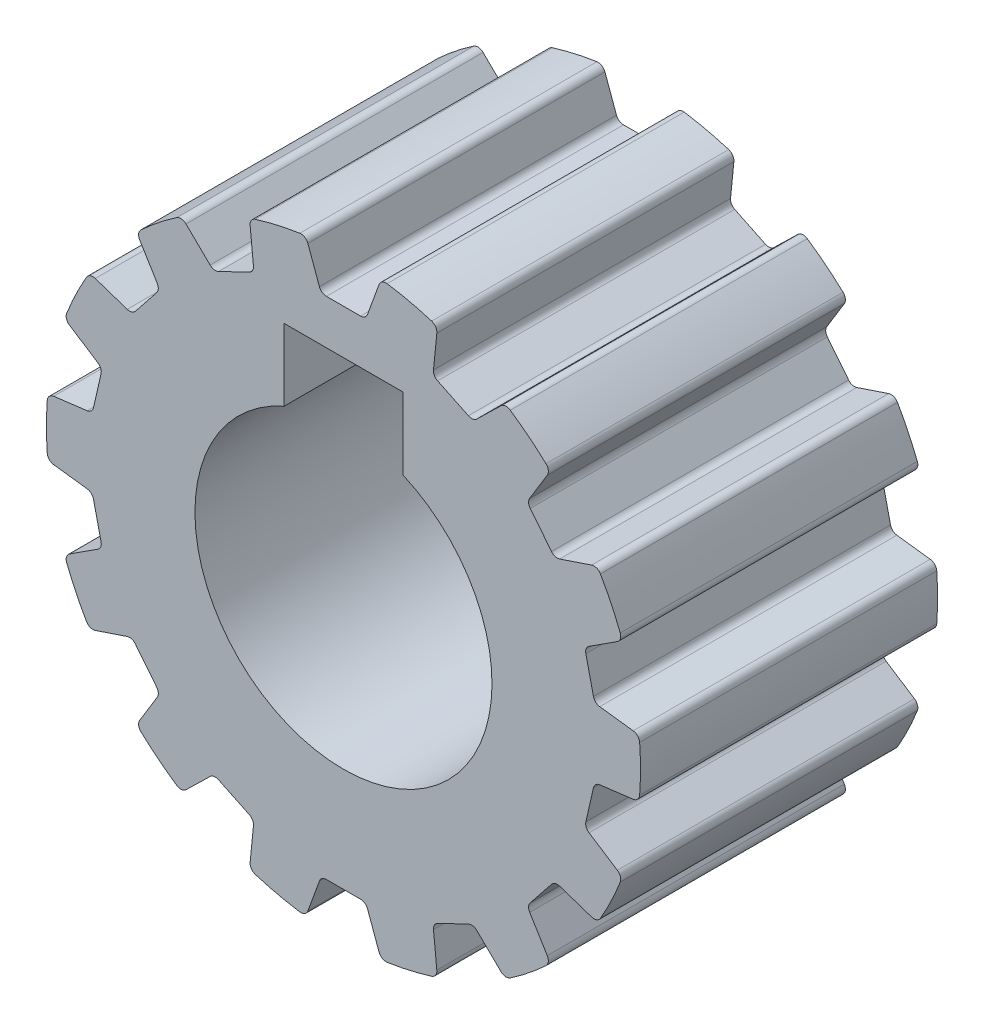
SolidWorks part; units mm, degrees
ref_plane "Front Plane" through (0, 0, 0) normal (0, 0, 1) x (1, 0, 0)
ref_plane "Top Plane" through (0, 0, 0) normal (0, 1, 0) x (1, 0, 0)
ref_plane "Right Plane" through (0, 0, 0) normal (1, 0, 0) x (0, 0, -1)
sketch "Sketch1" plane through (0, 0, 0) normal (0, 0, 1) x (1, 0, 0)
  line L0 (0, 0) -> (0, 6.4182) construction
  line L3 (-2, 4.5826) -> (-2, 7)
  line L4 (-2, 7) -> (2, 7)
  line L5 (2, 4.5826) -> (2, 7)
  circle A0 centre (0, 0) radius 10
  arc A1 (-2, 4.5826) -> (2, 4.5826) centre (0, 0) ccw
  point P5 (0, 4.4893)
  dimension "D1" = 20
  dimension "D2" = 10
  dimension "D3" = 4
  dimension "D4" = 7
extrude "Boss-Extrude1" add sketch "Sketch1" along normal blind 10
sketch "Sketch2" plane through (0, 0, 10) normal (0, 0, 1) x (1, 0, 0)
  line L0 (0, 0) -> (0, 10) construction
  line L1 (-1.2666, 9.9195) -> (-0.75, 8.5)
  line L2 (-0.75, 8.5) -> (0.75, 8.5)
  line L3 (0.75, 8.5) -> (1.2666, 9.9195)
  circle A0 centre (0, 0) radius 10 construction
  circle A1 centre (0, 0) radius 10
  circle M6 centre (0, 0) radius 10
  dimension "D1" = 20
  dimension "D2" = 20
  dimension "D3" = 1.5
  dimension "D4" = 8.5
extrude "Cut-Extrude1" cut sketch "Sketch2" against normal through all contours L2 L0 A1 L1 | L0 L2 L3 M6
pattern_circular "CirPattern1" count 14 over 360 about axis through (0, 0, 0) along (0, 0, 1) of "Cut-Extrude1"
fillet "Fillet1" radius 0.25 56 edges at (5.4451, 8.3875, 5) (4.3637, 7.3328, 5) (3.0123, 7.9836, 5) (3.1627, 9.4867, 5) (1.2666, 9.9195, 5) (0.75, 8.5, 5) (-0.75, 8.5, 5) (-3.1627, 9.4867, 5) (-3.0123, 7.9836, 5) (-4.3637, 7.3328, 5) (-6.9656, 7.175, 5) (-6.178, 5.886, 5) (-7.1132, 4.7133, 5) (-8.5451, 5.1944, 5) (-9.3889, 3.4422, 5) (-8.12, 2.6226, 5) (-8.4538, 1.1602, 5) (-9.9526, 0.9724, 5) (-9.9526, -0.9724, 5) (-8.4538, -1.1602, 5) (-8.12, -2.6226, 5) (-9.3889, -3.4422, 5) (-8.5451, -5.1944, 5) (-7.1132, -4.7133, 5) (-6.178, -5.886, 5) (-6.9656, -7.175, 5) (-5.4451, -8.3875, 5) (-4.3637, -7.3328, 5) (-3.0123, -7.9836, 5) (-3.1627, -9.4867, 5) (-1.2666, -9.9195, 5) (-0.75, -8.5, 5) (0.75, -8.5, 5) (1.2666, -9.9195, 5) (3.1627, -9.4867, 5) (3.0123, -7.9836, 5) (4.3637, -7.3328, 5) (5.4451, -8.3875, 5) (6.9656, -7.175, 5) (6.178, -5.886, 5) (7.1132, -4.7133, 5) (8.5451, -5.1944, 5) (9.3889, -3.4422, 5) (8.12, -2.6226, 5) (8.4538, -1.1602, 5) (9.9526, -0.9724, 5) (9.9526, 0.9724, 5) (8.4538, 1.1602, 5) (8.12, 2.6226, 5) (9.3889, 3.4422, 5) (8.5451, 5.1944, 5) (7.1132, 4.7133, 5) (6.178, 5.886, 5) (6.9656, 7.175, 5) (-5.4451, 8.3875, 5) (-1.2666, 9.9195, 5)
